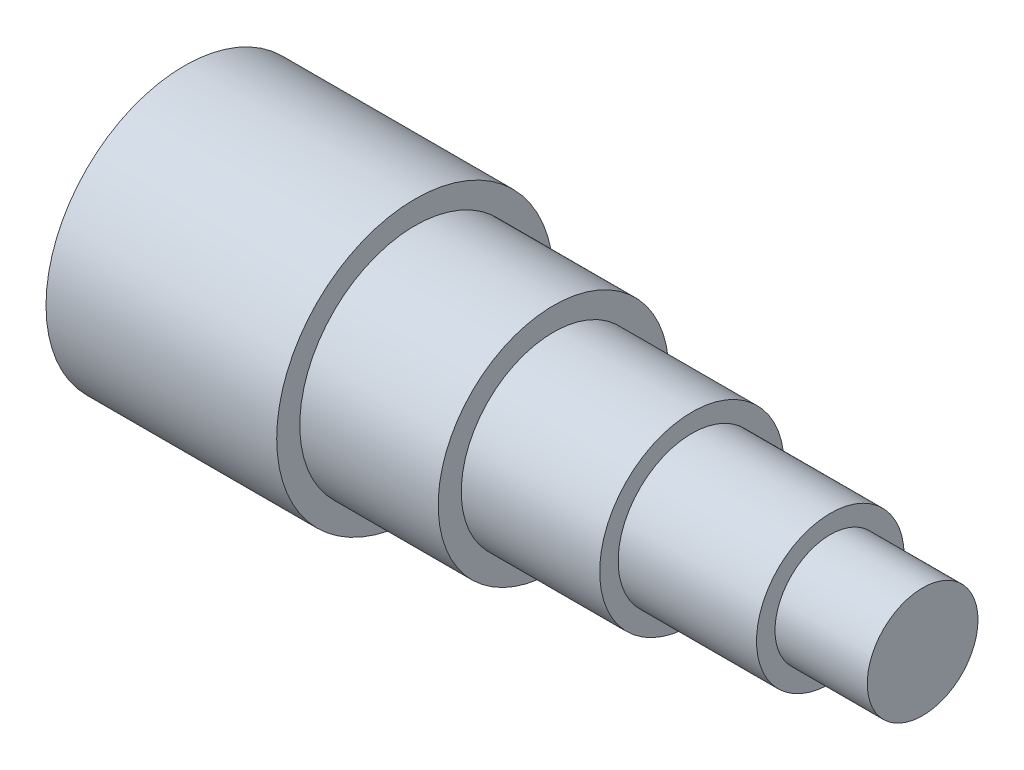
SolidWorks part; units mm, degrees
ref_plane "Front Plane" through (0, 0, 0) normal (0, 0, 1) x (1, 0, 0)
ref_plane "Top Plane" through (0, 0, 0) normal (0, 1, 0) x (1, 0, 0)
ref_plane "Right Plane" through (0, 0, 0) normal (1, 0, 0) x (0, 0, -1)
sketch "Sketch1" plane through (0, 0, 0) normal (1, 0, 0) x (0, 0, -1)
  circle A0 centre (0, 0) radius 15
  dimension "D1" = 30
extrude "Boss-Extrude1" add sketch "Sketch1" along normal blind 80
sketch "Sketch2" plane through (80, 0, 0) normal (1, 0, 0) x (0, 0, -1)
  circle A0 centre (0, 0) radius 15
  circle A1 centre (0, 0) radius 12.5
  dimension "D1" = 25
extrude "Cut-Extrude1" cut sketch "Sketch2" against normal blind 55
sketch "Sketch3" plane through (80, 0, 0) normal (1, 0, 0) x (0, 0, -1)
  circle A0 centre (0, 0) radius 12.5
  circle A1 centre (0, 0) radius 10
  dimension "D1" = 20
extrude "Cut-Extrude2" cut sketch "Sketch3" against normal blind 40
sketch "Sketch4" plane through (80, 0, 0) normal (1, 0, 0) x (0, 0, -1)
  circle A0 centre (0, 0) radius 10
  circle A1 centre (0, 0) radius 8
  dimension "D1" = 16
extrude "Cut-Extrude3" cut sketch "Sketch4" against normal blind 25
sketch "Sketch5" plane through (80, 0, 0) normal (1, 0, 0) x (0, 0, -1)
  circle A0 centre (0, 0) radius 8
  circle A1 centre (0, 0) radius 6
  dimension "D1" = 12
extrude "Cut-Extrude4" cut sketch "Sketch5" against normal blind 10
